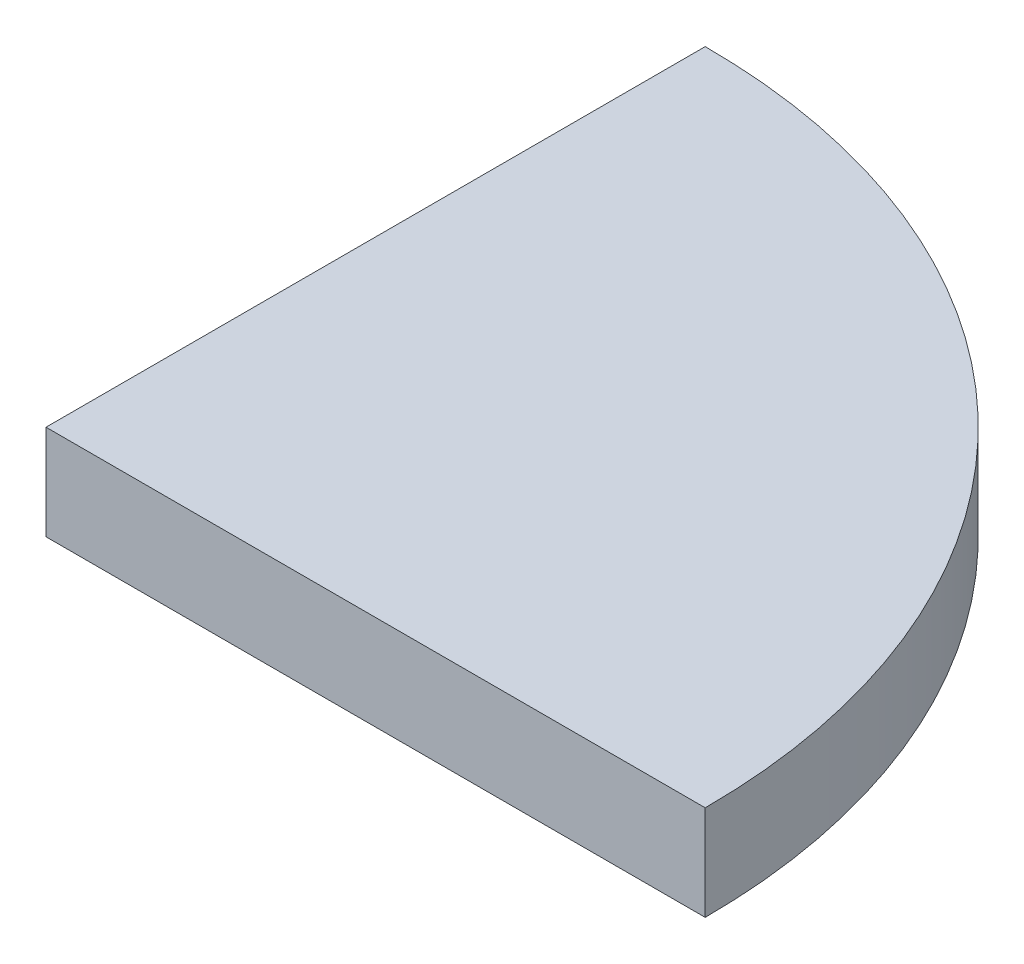
SolidWorks part; units mm, degrees
ref_plane "Plan de face" through (0, 0, 0) normal (0, 0, 1) x (1, 0, 0)
ref_plane "Plan de dessus" through (0, 0, 0) normal (0, 1, 0) x (1, 0, 0)
ref_plane "Plan de droite" through (0, 0, 0) normal (1, 0, 0) x (0, 0, -1)
sketch "Esquisse3" plane through (0, 0, 0) normal (0, 1, 0) x (1, 0, 0)
  line L0 (-49.8816, 223.5921) -> (-49.8816, -26.4079)
  line L1 (-49.8816, -26.4079) -> (200.1184, -26.4079)
  arc A0 (200.1184, -26.4079) -> (-49.8816, 223.5921) centre (-49.8816, -26.4079) ccw
  dimension "D1" = 250
  dimension "D2" = 250
extrude "Boss.-Extru.1" add sketch "Esquisse3" along normal blind 36 contours L1 A0 L0
